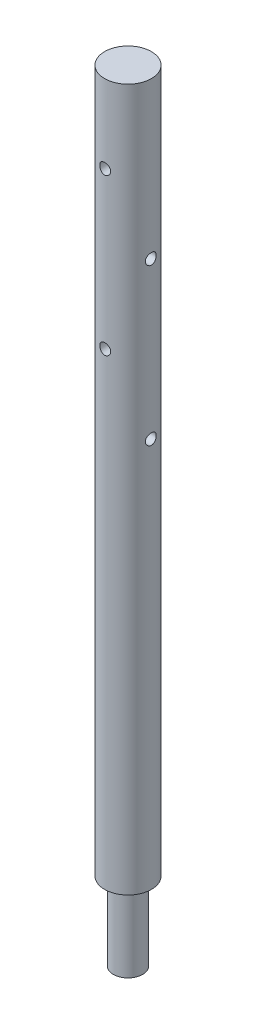
SolidWorks part; units mm, degrees
material "1060 Alloy"
ref_plane "Front Plane" through (0, 0, 0) normal (0, 0, 1) x (1, 0, 0)
ref_plane "Top Plane" through (0, 0, 0) normal (0, 1, 0) x (1, 0, 0)
ref_plane "Right Plane" through (0, 0, 0) normal (1, 0, 0) x (0, 0, -1)
sketch "Sketch1" plane through (0, 0, 0) normal (0, 1, 0) x (1, 0, 0)
  circle A0 centre (0, 0) radius 3.81
  dimension "D1" = 7.62
extrude "Boss-Extrude1" add sketch "Sketch1" along normal blind 127
sketch "Sketch2" plane through (0, 0, 0) normal (1, 0, 0) x (0, 0, -1)
  line L0 (0, 127) -> (0, 0) construction
  line L1 (3.81, 127) -> (-3.81, 127) construction
  circle A0 centre (0, 76.2) radius 0.889
  dimension "D2" = 1.778
  dimension "D1" = 50.8
ref_plane "Plane2" through (3.81, 0, 0) normal (1, 0, 0) x (0, 0, -1)
hole_wizard "#2-64 Tapped Hole1" positions "Sketch8" profile "Sketch9" tap size "#2-64" standard "ANSI Inch" end condition through all
sketch "Sketch8" plane through (3.81, 0, 0) normal (1, 0, 0) x (0, 0, -1)
  point P0 (0, 76.2)
sketch "Sketch9" plane through (3.81, 76.2, 0) normal (0, 1, 0) x (0, 0, -1)
  line L0 (0, 0) -> (0, 7.62)
  line L1 (0, 7.62) -> (0.889, 7.62)
  line L2 (0.889, 7.62) -> (0.889, 0)
  line L5 (0.889, 0) -> (0, 0)
  line L11 (0, -6.35) -> (0, 107.95) construction
  dimension "Thru Tap Drill Dia." = 1.778
  dimension "Thru Tap Drill Depth" = 7.62
cosmetic thread "Hole Thread1" parameters "D2"=2.1844
ref_plane "Plane3" through (0, 0, 3.81) normal (0, 0, 1) x (0, -1, 0)
sketch "Sketch10" plane through (0, 0, 3.81) normal (0, 0, 1) x (0, -1, 0)
  line L0 (-127, 0) -> (0, 0) construction
  line L3 (-127, 3.81) -> (-127, -3.81) construction
  circle A0 centre (-88.9, 0) radius 0.889
  dimension "D1" = 1.778
  dimension "D2" = 38.1
hole_wizard "#2-64 Tapped Hole2" positions "Sketch12" profile "Sketch13" tap size "#2-64" standard "ANSI Inch" end condition through all
sketch "Sketch12" plane through (0, 0, 3.81) normal (0, 0, 1) x (0, -1, 0)
  point P0 (-88.9, 0)
sketch "Sketch13" plane through (0, 88.9, 3.81) normal (1, 0, 0) x (0, -1, 0)
  line L0 (0, 0) -> (0, 7.62)
  line L1 (0, 7.62) -> (0.889, 7.62)
  line L2 (0.889, 7.62) -> (0.889, 0)
  line L5 (0.889, 0) -> (0, 0)
  line L11 (0, -6.35) -> (0, 107.95) construction
  dimension "Thru Tap Drill Dia." = 1.778
  dimension "Thru Tap Drill Depth" = 7.62
cosmetic thread "Hole Thread2" parameters "D2"=2.1844
pattern_linear "LPattern1" count 2 spacing 25.4 along (0, 1, 0) of "#2-64 Tapped Hole1"
pattern_linear "LPattern2" count 2 spacing 25.4 along (0, 1, 0) of "#2-64 Tapped Hole2"
ref_plane "Plane4" through (0, 0, -3.81) normal (0, 0, -1) x (-1, 0, 0)
ref_plane "Plane5" through (-3.81, 0, 0) normal (-1, 0, 0) x (0, 0, 1)
sketch "Sketch21" plane through (0, 0, 0) normal (0, -1, 0) x (1, 0, 0)
  circle A0 centre (0, 0) radius 3.81
  circle A1 centre (0, 0) radius 1.4224
  circle A2 centre (0, 0) radius 3.81 construction
  dimension "D1" = 2.8448
sketch "Sketch22" plane through (0, 0, 0) normal (0, -1, 0) x (1, 0, 0)
  circle A0 centre (0, 0) radius 2.3813
  circle A1 centre (0, 0) radius 3.81
  circle A2 centre (0, 0) radius 3.81 construction
  dimension "D1" = 4.7625
extrude "Cut-Extrude1" cut sketch "Sketch22" against normal blind 12.7
